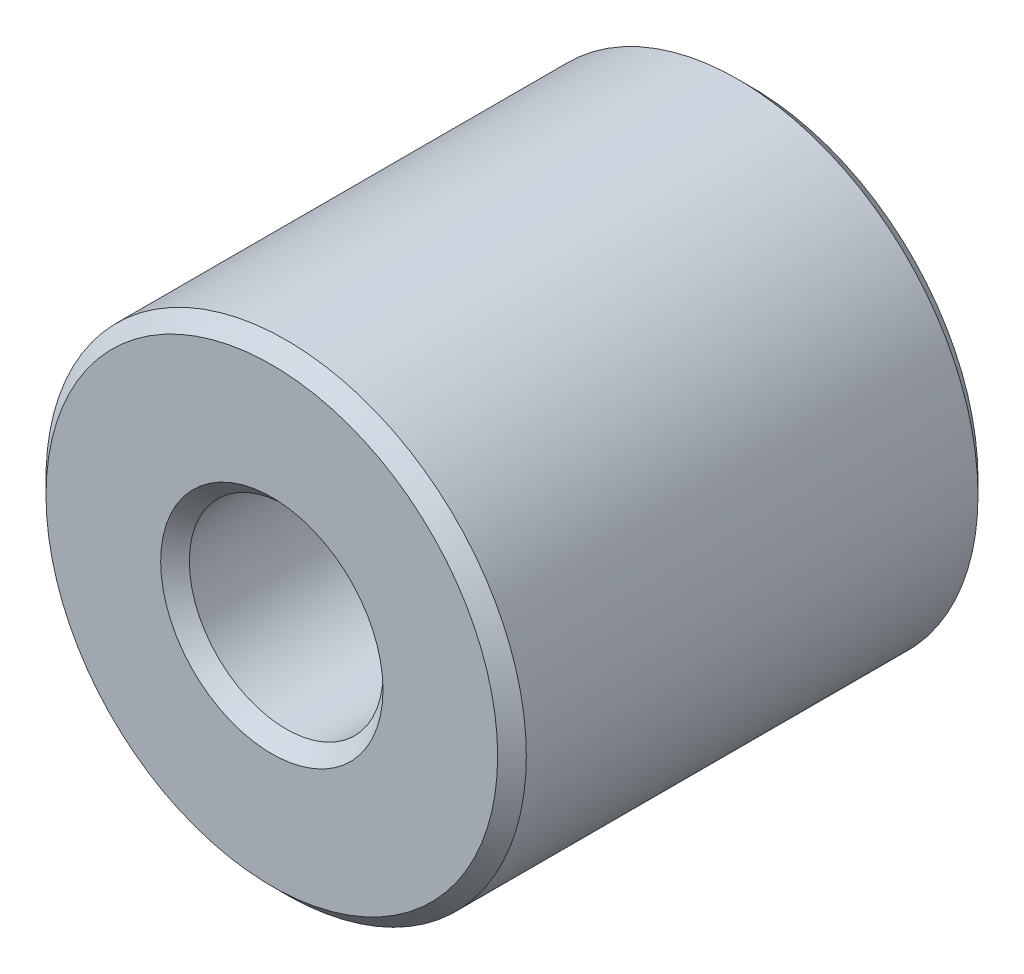
SolidWorks part; units mm, degrees
ref_plane "Front Plane" through (0, 0, 0) normal (0, 0, 1) x (1, 0, 0)
ref_plane "Top Plane" through (0, 0, 0) normal (0, 1, 0) x (1, 0, 0)
ref_plane "Right Plane" through (0, 0, 0) normal (1, 0, 0) x (0, 0, -1)
sketch "Sketch1" plane through (0, 0, 0) normal (0, 0, 1) x (1, 0, 0)
  circle A0 centre (0, 0) radius 7.9375 construction
  circle A1 centre (0, 0) radius 3.2004 construction
  point P4 (0, 7.9375)
  dimension "ID" = 6.4008
  dimension "OD" = 15.875
sketch "Sketch2" plane through (0, 0, 0) normal (1, 0, 0) x (0, 0, -1)
  line L0 (-7.9375, 7.9375) -> (7.9375, 7.9375) construction
  dimension "Length" = 15.875
sketch "Sketch3" plane through (0, 0, 0) normal (0, 0, 1) x (1, 0, 0)
  circle A0 centre (0, 0) radius 3.2004 construction
  circle A1 centre (0, 0) radius 7.9375 construction
  circle A2 centre (0, 0) radius 3.2004
  circle A3 centre (0, 0) radius 7.9375
extrude "Boss-Extrude1" add sketch "Sketch3" against normal up to vertex (7.9375 mm away) and the other way up to vertex (7.9375 mm away) up to point (0, 7.9375, -7.9375) other way up to point (0, 7.9375, 7.9375)
chamfer "Chamfer1" distance 0.4737 angle 45 4 edges at (7.9375, 0, 7.9375) (7.9375, 0, -7.9375) (3.2004, 0, 7.9375) (3.2004, 0, -7.9375)
equation "\"D1@Chamfer1\"=(\"OD@Sketch1\"-\"ID@Sketch1\")*0.05"
